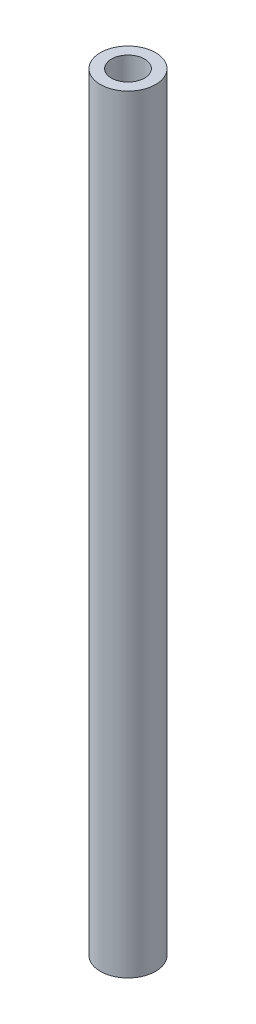
SolidWorks part; units mm, degrees
material "Brass"
ref_plane "Front Plane" through (0, 0, 0) normal (0, 0, 1) x (1, 0, 0)
ref_plane "Top Plane" through (0, 0, 0) normal (0, 1, 0) x (1, 0, 0)
ref_plane "Right Plane" through (0, 0, 0) normal (1, 0, 0) x (0, 0, -1)
sketch "Sketch1" plane through (0, 0, 0) normal (0, 1, 0) x (1, 0, 0)
  circle A0 centre (0, 0) radius 0.5
  dimension "D1" = 1
extrude "Boss-Extrude1" add sketch "Sketch1" along normal blind 13.9
hole_wizard "Ø0.4 (0.4) Diameter Hole1" positions "Sketch3" profile "Sketch2" hole size "Ø0.4" standard "Ansi Metric" end condition through all
sketch "Sketch3" plane through (0, 13.9, 0) normal (0, 1, 0) x (-1, 0, 0)
  point P0 (0, 0)
sketch "Sketch2" plane through (0, 13.9, 0) normal (1, 0, 0) x (0, 0, 1)
  line L0 (0, 0) -> (0, 13.9)
  line L1 (0, 13.9) -> (0.2, 13.9)
  line L2 (0.2, 13.9) -> (0.2, 0)
  line L5 (0.2, 0) -> (0, 0)
  line L11 (0, -6.35) -> (0, 107.95) construction
  dimension "Thru Hole Dia." = 0.4
  dimension "Thru Hole Depth" = 13.9
hole_wizard "Ø0.6 (0.6) Diameter Hole1" positions "Sketch5" profile "Sketch4" hole size "Ø0.6" standard "Ansi Metric"
sketch "Sketch5" plane through (0, 13.9, 0) normal (0, 1, 0) x (-1, 0, 0)
  point P0 (0, 0)
sketch "Sketch4" plane through (0, 13.9, 0) normal (1, 0, 0) x (0, 0, 1)
  line L0 (0, 0) -> (0, 3.1803)
  line L1 (0, 3.1803) -> (0.3, 3)
  line L2 (0.3, 3) -> (0.3, 0)
  line L5 (0.3, 0) -> (0, 0)
  line L10 (0, 3.1803) -> (-0.3, 3) construction
  line L11 (0, -6.35) -> (0, 107.95) construction
  dimension "Hole Dia." = 0.6
  dimension "Hole Depth" = 3
  dimension "Drill Angle" = 118
hole_wizard "Ø0.6 (0.6) Diameter Hole2" positions "Sketch7" profile "Sketch6" hole size "Ø0.6" standard "Ansi Metric"
sketch "Sketch7" plane through (0, 0, 0) normal (0, -1, 0) x (1, 0, 0)
  point P0 (0, 0)
sketch "Sketch6" plane through (0, 0, 0) normal (1, 0, 0) x (0, 0, -1)
  line L0 (0, 0) -> (0, 3.1803)
  line L1 (0, 3.1803) -> (0.3, 3)
  line L2 (0.3, 3) -> (0.3, 0)
  line L5 (0.3, 0) -> (0, 0)
  line L10 (0, 3.1803) -> (-0.3, 3) construction
  line L11 (0, -6.35) -> (0, 107.95) construction
  dimension "Hole Dia." = 0.6
  dimension "Hole Depth" = 3
  dimension "Drill Angle" = 118
